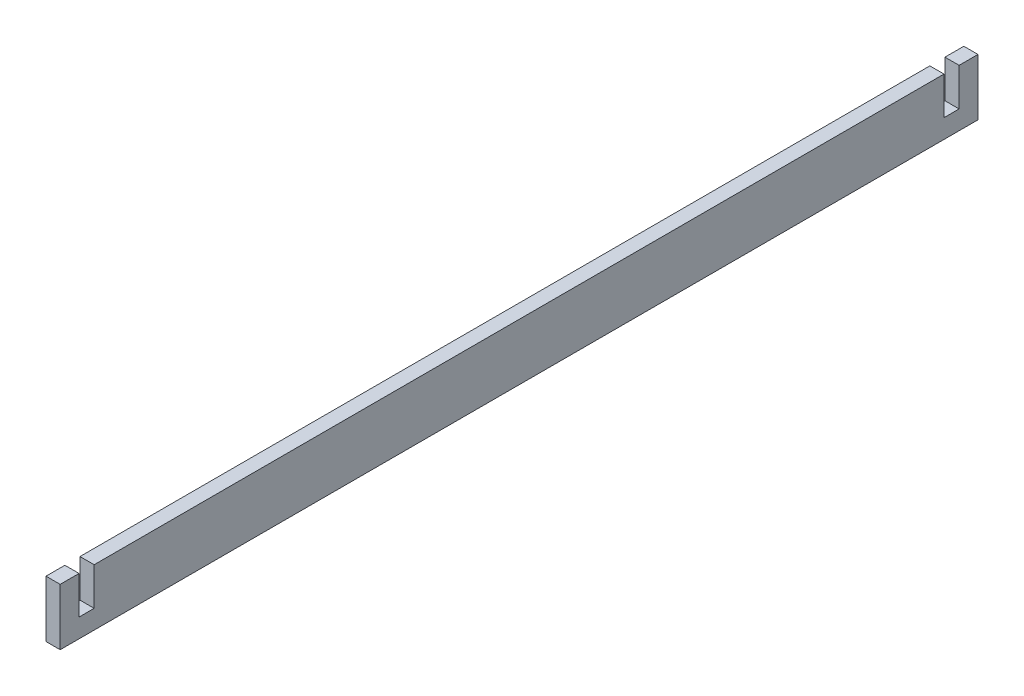
SolidWorks part; units mm, degrees
ref_plane "Front Plane" through (0, 0, 0) normal (0, 0, 1) x (1, 0, 0)
ref_plane "Top Plane" through (0, 0, 0) normal (0, 1, 0) x (1, 0, 0)
ref_plane "Right Plane" through (0, 0, 0) normal (1, 0, 0) x (0, 0, -1)
sketch "Sketch1" plane through (0, 0, 0) normal (1, 0, 0) x (0, 0, -1)
  line L0 (-97.2, 12) -> (-97.2, 0)
  line L1 (-97.2, 0) -> (97.2, 0)
  line L2 (97.2, 0) -> (97.2, 12)
  line L3 (97.2, 12) -> (93.2, 12)
  line L4 (93.2, 12) -> (93.2, 4)
  line L5 (93.2, 4) -> (90, 4)
  line L6 (90, 4) -> (90, 12)
  line L7 (90, 12) -> (-90, 12)
  line L8 (-90, 12) -> (-90, 4)
  line L9 (-90, 4) -> (-93.2, 4)
  line L10 (-93.2, 4) -> (-93.2, 12)
  line L11 (-93.2, 12) -> (-97.2, 12)
  point P13 (0, 0)
  dimension "D1" = 12
  dimension "D2" = 8
  dimension "D3" = 4
  dimension "D4" = 3.2
  dimension "D5" = 180
extrude "Boss-Extrude1" add sketch "Sketch1" along normal blind 3
equation "\"mdfWidth\"= 3"
equation "\"cellSide\"= 180"
equation "\"mazeHeight\" = 50"
equation "\"slitHeight\"= 10"
equation "\"gripWidth\"= 6"
equation "\"wallThickness\"= 1.5"
equation "\"slitWidth\" = \"wallThickness\""
equation "\"play\"= 0.2"
equation "\"D4@Sketch1\"= \"mdfWidth\" + \"play\""
equation "\"D5@Sketch1\"= \"cellSide\""
equation "\"D1@Boss-Extrude1\"= \"mdfWidth\""
